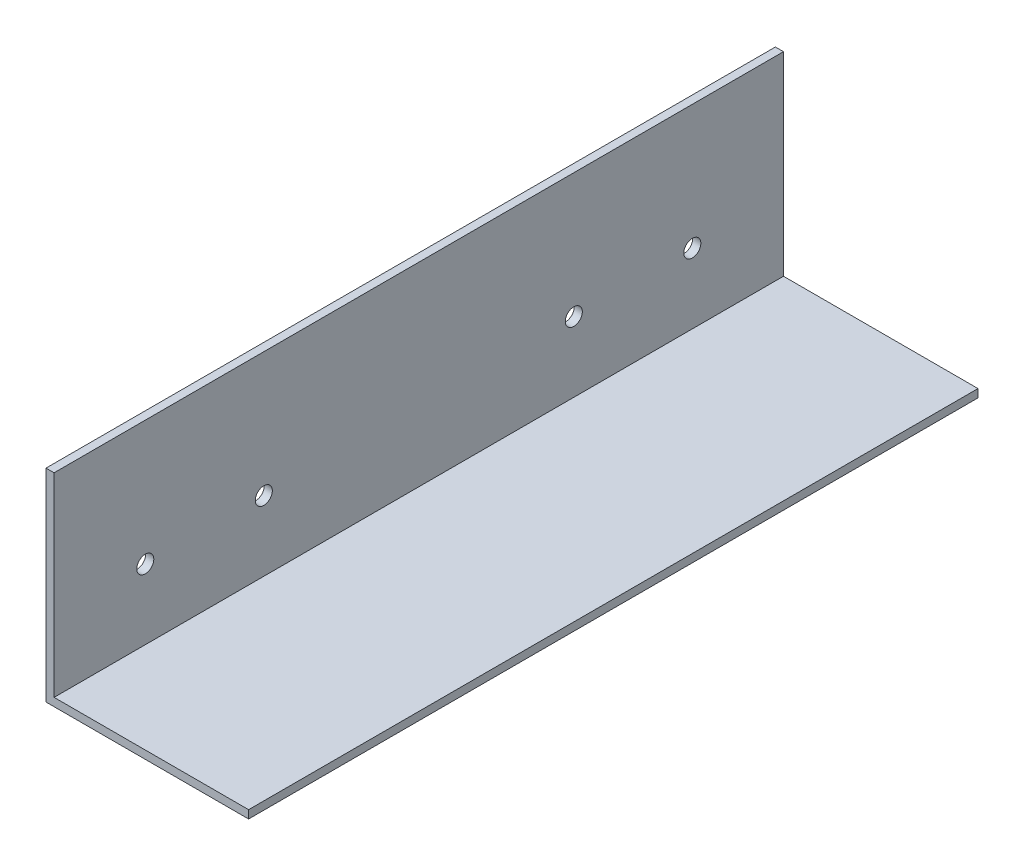
SolidWorks part; units mm, degrees
ref_plane "Front Plane" through (0, 0, 0) normal (0, 0, 1) x (1, 0, 0)
ref_plane "Top Plane" through (0, 0, 0) normal (0, 1, 0) x (1, 0, 0)
ref_plane "Right Plane" through (0, 0, 0) normal (1, 0, 0) x (0, 0, -1)
sketch "Sketch1" plane through (0, 0, 0) normal (0, 0, 1) x (1, 0, 0)
  line L0 (0, 0) -> (50, 0)
  line L1 (50, 0) -> (50, 2)
  line L2 (50, 2) -> (2, 2)
  line L3 (2, 2) -> (2, 50)
  line L4 (2, 50) -> (0, 50)
  line L5 (0, 50) -> (0, 0)
  dimension "D1" = 50
  dimension "D2" = 50
  dimension "D3" = 2
  dimension "D4" = 2
extrude "Boss-Extrude1" add sketch "Sketch1" along normal blind 180
sketch "Sketch2" plane through (0, 0, 0) normal (1, 0, 0) x (0, 0, -1)
  circle A0 centre (-22.5, 19.25) radius 2.1
  circle A1 centre (-51.75, 19.25) radius 2.1
  circle A2 centre (-128.25, 19.25) radius 2.1
  circle A3 centre (-157.5, 19.25) radius 2.1
  dimension "D1" = 4.2
  dimension "D2" = 19.25
  dimension "D3" = 22.5
  dimension "D4" = 51.75
  dimension "D5" = 128.25
  dimension "D6" = 157.5
extrude "Cut-Extrude1" cut sketch "Sketch2" against normal mid plane 10
